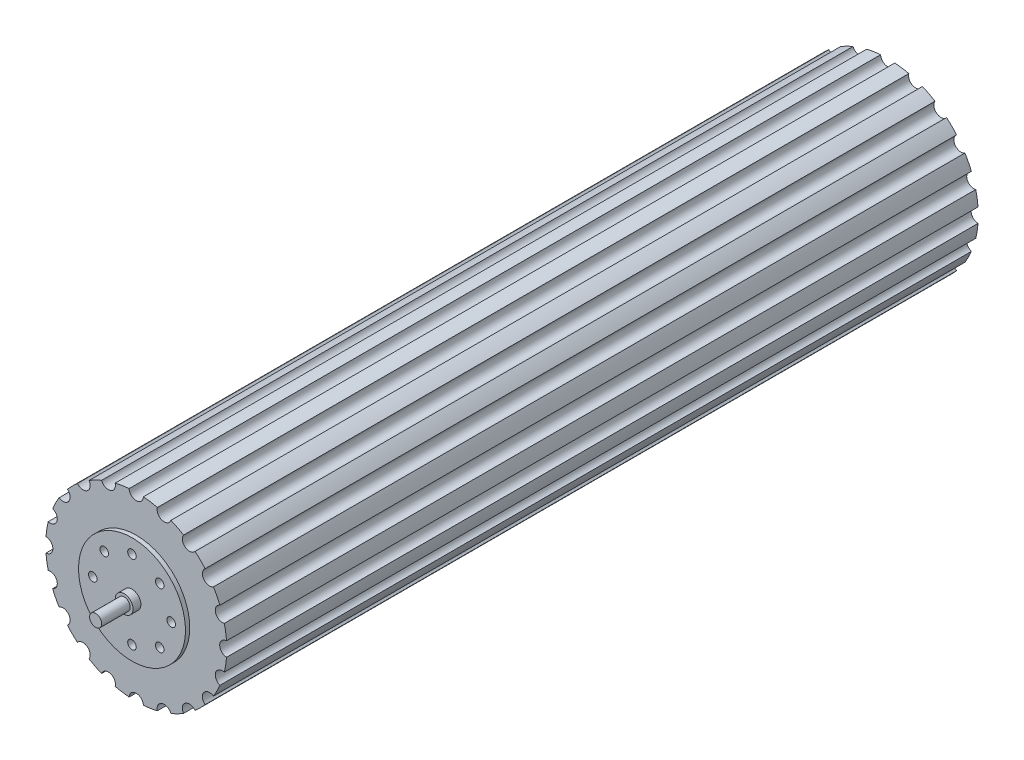
SolidWorks part; units mm, degrees
ref_plane "Front Plane" through (0, 0, 0) normal (0, 0, 1) x (1, 0, 0)
ref_plane "Top Plane" through (0, 0, 0) normal (0, 1, 0) x (1, 0, 0)
ref_plane "Right Plane" through (0, 0, 0) normal (1, 0, 0) x (0, 0, -1)
sketch "Sketch1" plane through (0, 0, 0) normal (0, 0, 1) x (1, 0, 0)
  circle A0 centre (0, 0) radius 127
  dimension "D1" = 254
extrude "Boss-Extrude1" add sketch "Sketch1" along normal mid plane 1054
ref_plane "Plane1" through (0, 0, 0) normal (0, 0, -1) x (-1, 0, 0)
sketch "Sketch4" plane through (0, 0, 0) normal (0, 0, -1) x (-1, 0, 0)
  circle A0 centre (0, 0) radius 12.5
  dimension "D1" = 25
extrude "Boss-Extrude3" add sketch "Sketch4" along normal mid plane 1168
sketch "Sketch5" plane through (0, 0, -527) normal (0, 0, -1) x (-1, 0, 0)
  circle A0 centre (0, 0) radius 75
  circle A1 centre (0, 0) radius 12.5 construction
  circle A2 centre (0, 0) radius 12.5
  dimension "D1" = 150
extrude "Boss-Extrude4" add sketch "Sketch5" along normal blind 6
mirror "Mirror1" about plane through (0, 0, 0) normal (0, 0, -1) of "Boss-Extrude4", "Boss-Extrude3"
sketch "Sketch6" plane through (0, 0, -533) normal (0, 0, -1) x (-1, 0, 0)
  circle A0 centre (0, 0) radius 55
  circle A1 centre (0, 55) radius 6
  circle A2 centre (38.8909, 38.8909) radius 6
  circle A3 centre (55, 0) radius 6
  circle A4 centre (38.8909, -38.8909) radius 6
  circle A5 centre (0, -55) radius 6
  circle A6 centre (-38.8909, -38.8909) radius 6
  circle A7 centre (-55, 0) radius 6
  circle A8 centre (-38.8909, 38.8909) radius 6
  dimension "D1" = 110
  dimension "D2" = 12
  dimension "D3" = 8
extrude "Cut-Extrude1" cut sketch "Sketch6" against normal through all both and the other way through all contours A2 | A8 | A7 | A6 | A5 | A4 | A3 | A1
sketch "Sketch7" plane through (0, 0, -527) normal (0, 0, -1) x (-1, 0, 0)
  circle A0 centre (0, 127) radius 10
  circle A1 centre (0, 0) radius 127 construction
  circle A2 centre (39.2452, 120.7842) radius 10
  circle A3 centre (74.6487, 102.7452) radius 10
  circle A4 centre (102.7452, 74.6487) radius 10
  circle A5 centre (120.7842, 39.2452) radius 10
  circle A6 centre (127, 0) radius 10
  circle A7 centre (120.7842, -39.2452) radius 10
  circle A8 centre (102.7452, -74.6487) radius 10
  circle A9 centre (74.6487, -102.7452) radius 10
  circle A10 centre (39.2452, -120.7842) radius 10
  circle A11 centre (0, -127) radius 10
  circle A12 centre (-39.2452, -120.7842) radius 10
  circle A13 centre (-74.6487, -102.7452) radius 10
  circle A14 centre (-102.7452, -74.6487) radius 10
  circle A15 centre (-120.7842, -39.2452) radius 10
  circle A16 centre (-127, 0) radius 10
  circle A17 centre (-120.7842, 39.2452) radius 10
  circle A18 centre (-102.7452, 74.6487) radius 10
  circle A19 centre (-74.6487, 102.7452) radius 10
  circle A20 centre (-39.2452, 120.7842) radius 10
  dimension "D1" = 20
  dimension "D2" = 20
extrude "Cut-Extrude2" cut sketch "Sketch7" against normal through all both and the other way through all
sketch "Sketch8" plane through (0, 0, -584) normal (0, 0, -1) x (-1, 0, 0)
  circle A0 centre (0, 0) radius 8.5
  circle M1 centre (0, 0) radius 12.5
  dimension "D1" = 17
extrude "Cut-Extrude4" cut sketch "Sketch8" against normal blind 40 contours A0 M1
sketch "Sketch10" plane through (0, 0, 584) normal (0, 0, 1) x (1, 0, 0)
  circle A0 centre (0, 0) radius 8.5
  circle M2 centre (0, 0) radius 12.5
  dimension "D1" = 17
extrude "Cut-Extrude5" cut sketch "Sketch10" against normal blind 40 contours A0 M2
